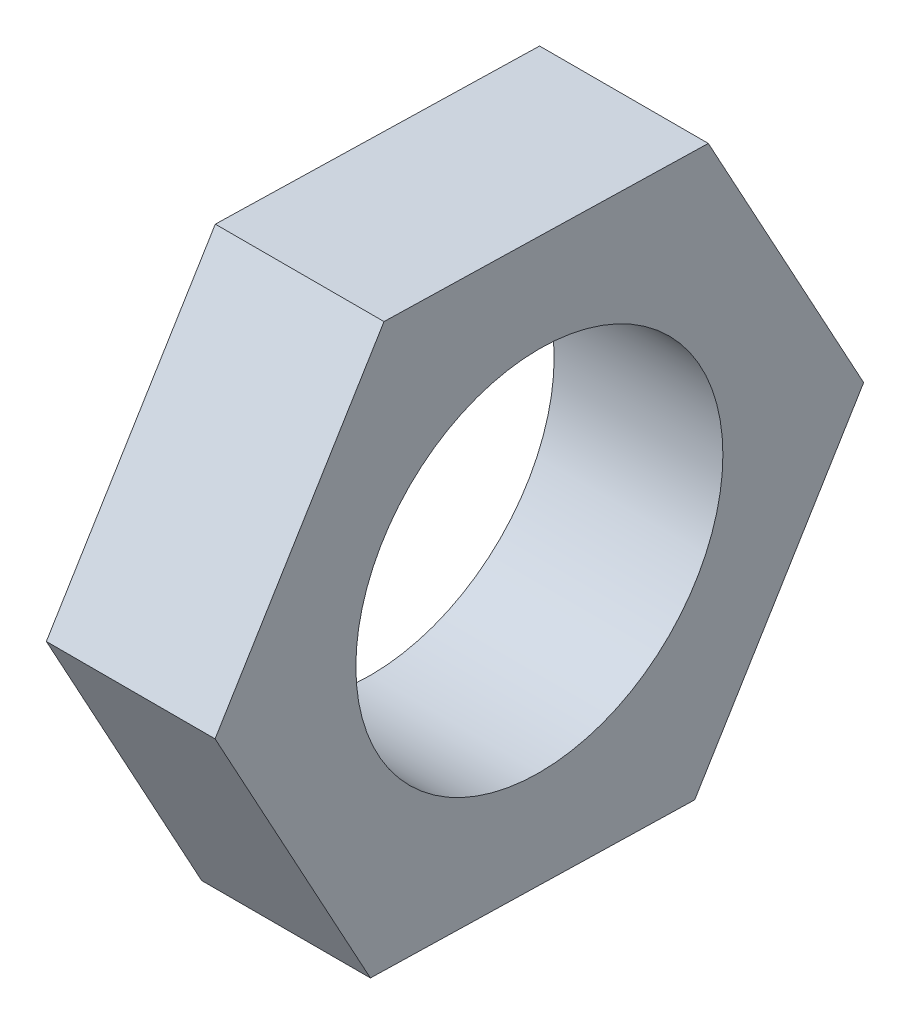
SolidWorks part; units mm, degrees
ref_plane "Front Plane" through (0, 0, 0) normal (0, 0, 1) x (1, 0, 0)
ref_plane "Top Plane" through (0, 0, 0) normal (0, 1, 0) x (1, 0, 0)
ref_plane "Right Plane" through (0, 0, 0) normal (1, 0, 0) x (0, 0, -1)
sketch "Sketch1" plane through (0, 0, 0) normal (1, 0, 0) x (0, 0, -1)
  line L1 (345.9112, 35.5892) -> (354.6483, 19.5722)
  line L2 (354.6483, 19.5722) -> (372.888, 19.1302)
  line L3 (372.888, 19.1302) -> (382.3906, 34.7053)
  line L4 (382.3906, 34.7053) -> (373.6535, 50.7223)
  line L5 (373.6535, 50.7223) -> (355.4138, 51.1643)
  line L6 (355.4138, 51.1643) -> (345.9112, 35.5892)
  circle A0 centre (364.1509, 35.1472) radius 10.3228
  circle A1 centre (364.1509, 35.1472) radius 15.8007 construction
  point P2 (353.8281, 35.1472)
extrude "Boss-Extrude1" add sketch "Sketch1" against normal blind 9.4902
